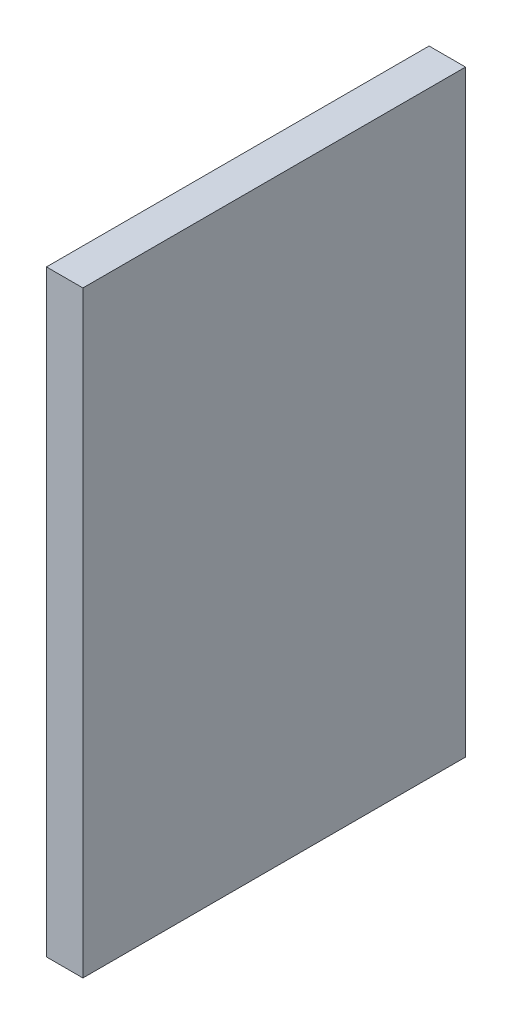
SolidWorks part; units mm, degrees
ref_plane "Front Plane" through (0, 0, 0) normal (0, 0, 1) x (1, 0, 0)
ref_plane "Top Plane" through (0, 0, 0) normal (0, 1, 0) x (1, 0, 0)
ref_plane "Right Plane" through (0, 0, 0) normal (1, 0, 0) x (0, 0, -1)
sketch "Sketch1" plane through (0, 0, 0) normal (0, 1, 0) x (1, 0, 0)
  line L1 (-19.05, 187.325) -> (19.05, 187.325)
  line L2 (-19.05, 187.325) -> (-19.05, -212.725)
  line L3 (-19.05, -212.725) -> (19.05, -212.725)
  line L4 (19.05, 187.325) -> (19.05, -212.725)
  dimension "D1" = 38.1
  dimension "D2" = 400.05
  dimension "D3" = 19.05
  dimension "D4" = 187.325
extrude "Boss-Extrude1" add sketch "Sketch1" along normal mid plane 624.84
